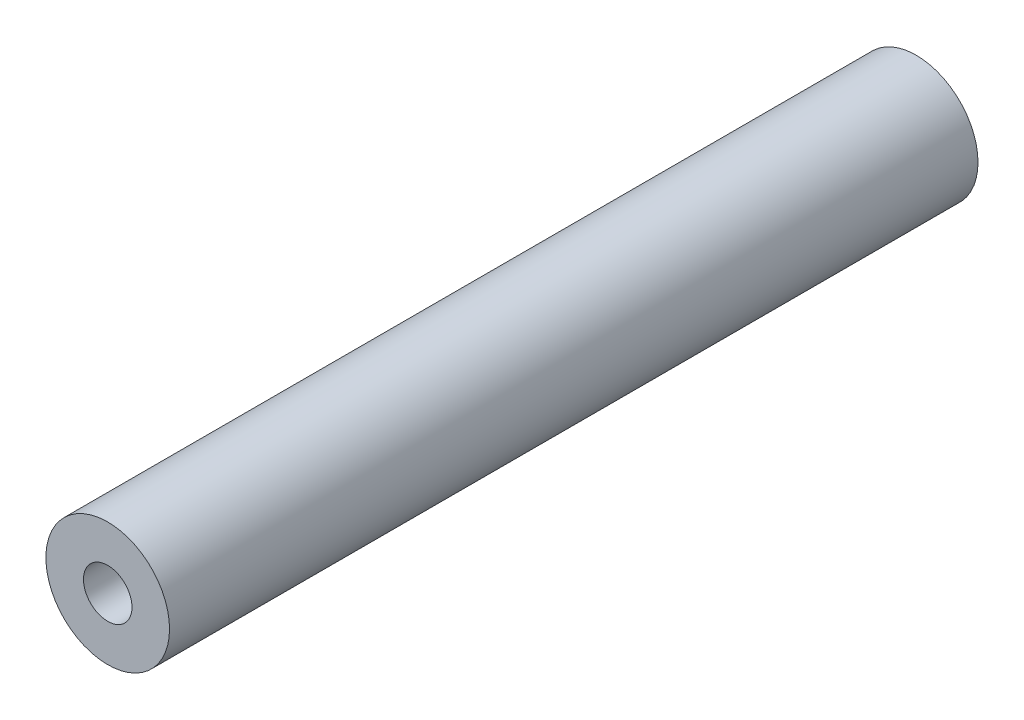
SolidWorks part; units mm, degrees
ref_plane "Front Plane" through (0, 0, 0) normal (0, 0, 1) x (1, 0, 0)
ref_plane "Top Plane" through (0, 0, 0) normal (0, 1, 0) x (1, 0, 0)
ref_plane "Right Plane" through (0, 0, 0) normal (1, 0, 0) x (0, 0, -1)
sketch "Sketch1" plane through (0, 0, 0) normal (0, 0, 1) x (1, 0, 0)
  circle A0 centre (0, 0) radius 2.55
  circle A1 centre (0, 0) radius 6.5
  dimension "D1" = 5.1
  dimension "D2" = 13
extrude "Boss-Extrude1" add sketch "Sketch1" along normal blind 85
